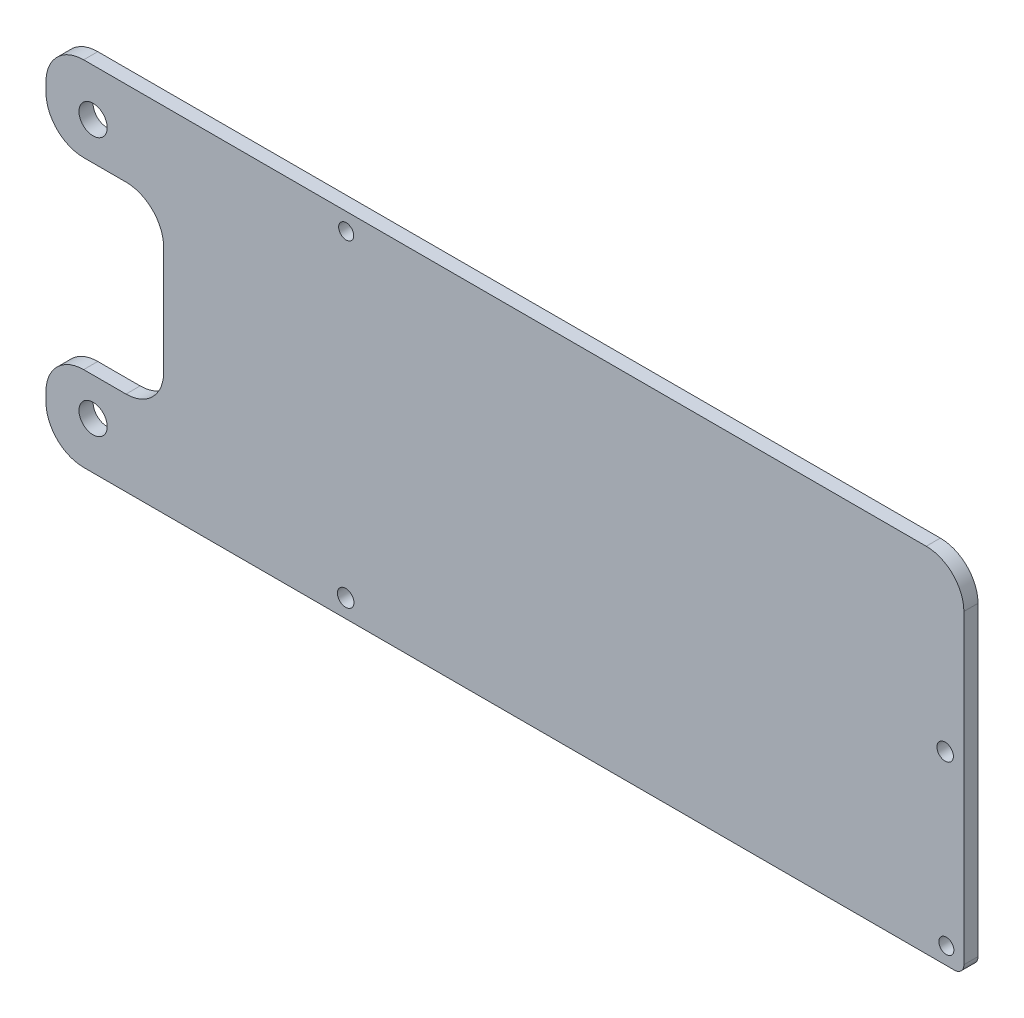
SolidWorks part; units mm, degrees
material "Acrylic (Medium-high impact)"
ref_plane "Front Plane" through (0, 0, 0) normal (0, 0, 1) x (1, 0, 0)
ref_plane "Top Plane" through (0, 0, 0) normal (0, 1, 0) x (1, 0, 0)
ref_plane "Right Plane" through (0, 0, 0) normal (1, 0, 0) x (0, 0, -1)
ref_plane "Dielectric_Layer Layer 1" through (0, 0, 0.3912) normal (0, 0, 1) x (1, 0, 0)
sketch "Sketch1" plane through (0, 0, 0) normal (0, 0, 1) x (1, 0, 0)
  line L0 (10, 10) -> (10, 85)
  line L1 (10, 85) -> (145, 85)
  line L2 (145, 85) -> (145, 10)
  line L3 (145, 10) -> (10, 10)
sketch "Sketch2" plane through (0, 0, 0) normal (0, 0, 1) x (1, 0, 0)
  circle A0 centre (14.9528, 21.3713) radius 0.45
  circle A1 centre (14.9528, 25.7712) radius 0.45
sketch "Sketch3" plane through (0, 0, 0) normal (0, 0, 1) x (1, 0, 0)
  line L0 (-40, 85) -> (-40, 10) construction
  line L1 (10, 85) -> (145, 85)
  line L2 (10, 85) -> (10, 10)
  line L3 (10, 10) -> (145, 10)
  line L4 (145, 85) -> (145, 10)
  line L5 (10, 85) -> (-50, 85)
  line L6 (10, 85) -> (10, 10)
  line L7 (10, 10) -> (-50, 10)
  line L8 (-50, 85) -> (-50, 10)
  line L10 (-50, 67) -> (-25, 67)
  line L11 (-50, 67) -> (-50, 28)
  line L12 (-50, 28) -> (-25, 28)
  line L13 (-25, 67) -> (-25, 28)
  circle A211 centre (13.6652, 13.843) radius 1.75
  circle A253 centre (13.7726, 81.3248) radius 1.6
  circle A254 centre (141.0208, 49.2252) radius 1.75
  circle A306 centre (141.2748, 13.6144) radius 1.6
  circle A527 centre (-40, 75) radius 3
  circle A528 centre (-40, 20) radius 3
  dimension "D3" = 6
  dimension "D1" = 60
  dimension "D2" = 10
  dimension "D4" = 10
  dimension "D5" = 10
  dimension "D6" = 8
  dimension "D7" = 8
  dimension "D8" = 25
extrude "Boss-Extrude1" add sketch "Sketch3" along normal blind 3 contours L5 L0 A527 L10 L13 L12 A528 L7 L2 | L0 L5 L8 L10 A527 | L0 L12 L8 L7 A528 | L4 L1 L2 L3 A306 A254 A253 A211
fillet "Fillet1" radius 8 7 edges at (145, 85, 1.5) (-50, 67, 1.5) (-50, 85, 1.5) (-50, 10, 1.5) (-50, 28, 1.5) (-25, 28, 1.5) (-25, 67, 1.5)
fillet "Fillet2" radius 2 1 edges at (145, 10, 1.5)
